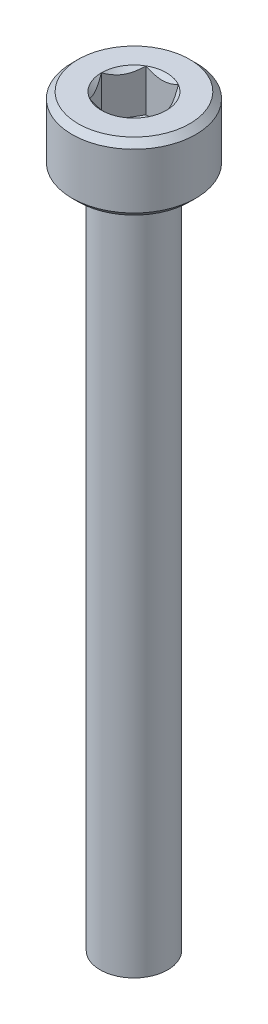
SolidWorks part; units mm, degrees
ref_plane "Front" through (0, 0, 0) normal (0, 0, 1) x (1, 0, 0)
ref_plane "Top" through (0, 0, 0) normal (0, 1, 0) x (1, 0, 0)
ref_plane "Right" through (0, 0, 0) normal (1, 0, 0) x (0, 0, -1)
sketch "Sketch1" plane through (0, 0, 0) normal (0, 1, 0) x (1, 0, 0)
  circle A0 centre (0, 0) radius 2.75
  dimension "D1" = 5.5
extrude "Boss-Extrude1" add sketch "Sketch1" along normal blind 3
sketch "Sketch2" plane through (0, 3, 0) normal (0, 1, 0) x (1, 0, 0)
  line L1 (0.7217, 1.25) -> (-0.7217, 1.25)
  line L2 (-0.7217, 1.25) -> (-1.4434, 0)
  line L3 (-1.4434, 0) -> (-0.7217, -1.25)
  line L4 (-0.7217, -1.25) -> (0.7217, -1.25)
  line L5 (0.7217, -1.25) -> (1.4434, 0)
  line L6 (1.4434, 0) -> (0.7217, 1.25)
  circle A0 centre (0, 0) radius 1.25 construction
  point P10 (0, 1.25)
  dimension "D1" = 2.5
extrude "Cut-Extrude1" cut sketch "Sketch2" against normal blind 1.88
sketch "Sketch5" plane through (0, 3, 0) normal (0, 1, 0) x (1, 0, 0)
  circle A0 centre (0, 0) radius 1.4434
extrude "Cut-Extrude2" cut sketch "Sketch5" against normal through all draft 45
chamfer "Chamfer1" distance 0.275 angle 45 2 edges at (0, 0, 2.75) (0, 3, 2.75)
sketch "草图1" plane through (0, 0, 0) normal (0, -1, 0) x (-1, 0, 0)
  circle A0 centre (0, 0) radius 1.5
  dimension "D1" = 3
extrude "凸台-拉伸1" add sketch "草图1" along normal blind 30
